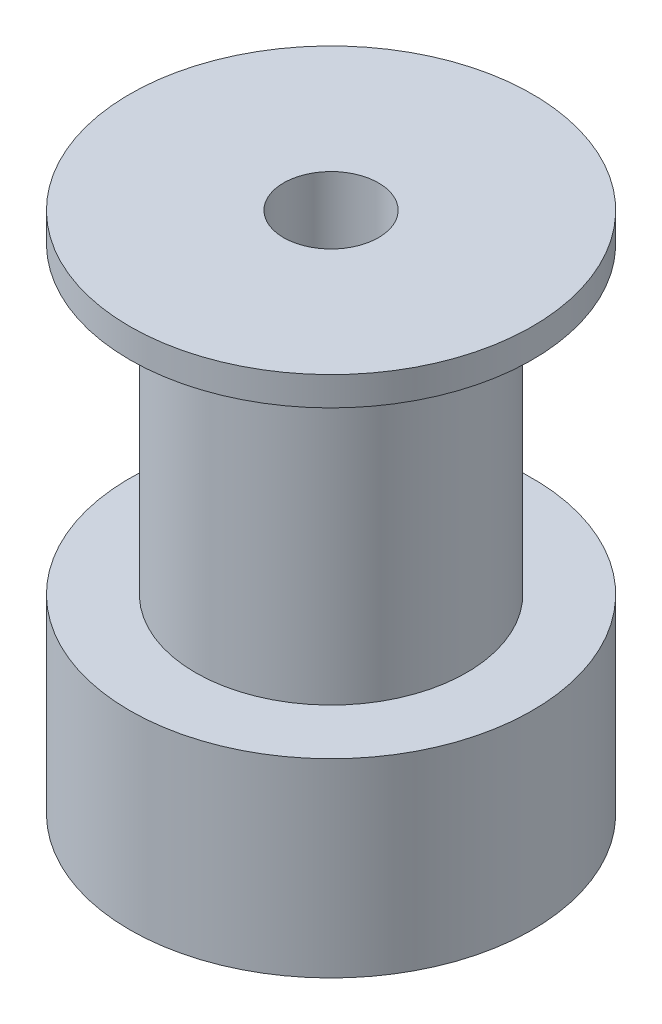
SolidWorks part; units mm, degrees
ref_plane "Front Plane" through (0, 0, 0) normal (0, 0, 1) x (1, 0, 0)
ref_plane "Top Plane" through (0, 0, 0) normal (0, 1, 0) x (1, 0, 0)
ref_plane "Right Plane" through (0, 0, 0) normal (1, 0, 0) x (0, 0, -1)
sketch "Sketch1" plane through (0, 0, 0) normal (0, 1, 0) x (1, 0, 0)
  circle A0 centre (0, 0) radius 6.731
  dimension "D1" = 13.462
extrude "Boss-Extrude1" add sketch "Sketch1" along normal blind 17.4752
sketch "Sketch2" plane through (0, 0, 0) normal (1, 0, 0) x (0, 0, -1)
  line L0 (0, 18.3093) -> (0, 0) construction
  line L1 (6.731, 0) -> (6.731, 17.4752) construction
  line L2 (6.731, 16.51) -> (4.5339, 16.51)
  line L3 (6.731, 16.51) -> (6.731, 6.35)
  line L4 (6.731, 6.35) -> (4.5339, 6.35)
  line L5 (4.5339, 16.51) -> (4.5339, 6.35)
  line L6 (-6.731, 0) -> (6.731, 0) construction
  point P9 (5.6325, 6.35)
  dimension "D1" = 10.16
  dimension "D2" = 6.35
  dimension "D3" = 9.0678
revolve "Cut-Revolve1" cut sketch "Sketch2" angle 360 about L0
sketch "Sketch3" plane through (0, 17.4752, 0) normal (0, 1, 0) x (1, 0, 0)
  circle A0 centre (0, 0) radius 1.5875
  dimension "D1" = 3.175
extrude "Cut-Extrude1" cut sketch "Sketch3" against normal blind 17.4752
